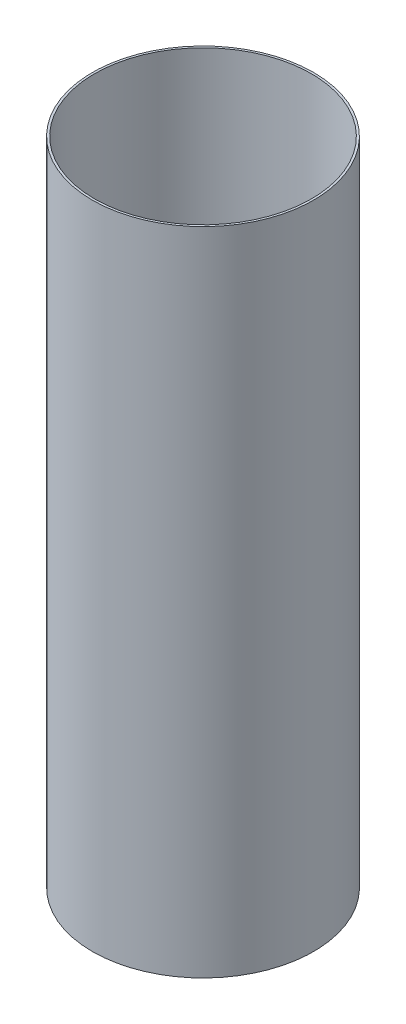
SolidWorks part; units mm, degrees
ref_plane "Alzado" through (0, 0, 0) normal (0, 0, 1) x (1, 0, 0)
ref_plane "Planta" through (0, 0, 0) normal (0, 1, 0) x (1, 0, 0)
ref_plane "Vista lateral" through (0, 0, 0) normal (1, 0, 0) x (0, 0, -1)
sketch "Sketch1" plane through (0, 0, 0) normal (0, 1, 0) x (1, 0, 0)
  circle A0 centre (0, 0) radius 51
  circle A1 centre (0, 0) radius 50
  dimension "D1" = 102
  dimension "D2" = 100
extrude "Boss-Extrude1" add sketch "Sketch1" along normal blind 300
